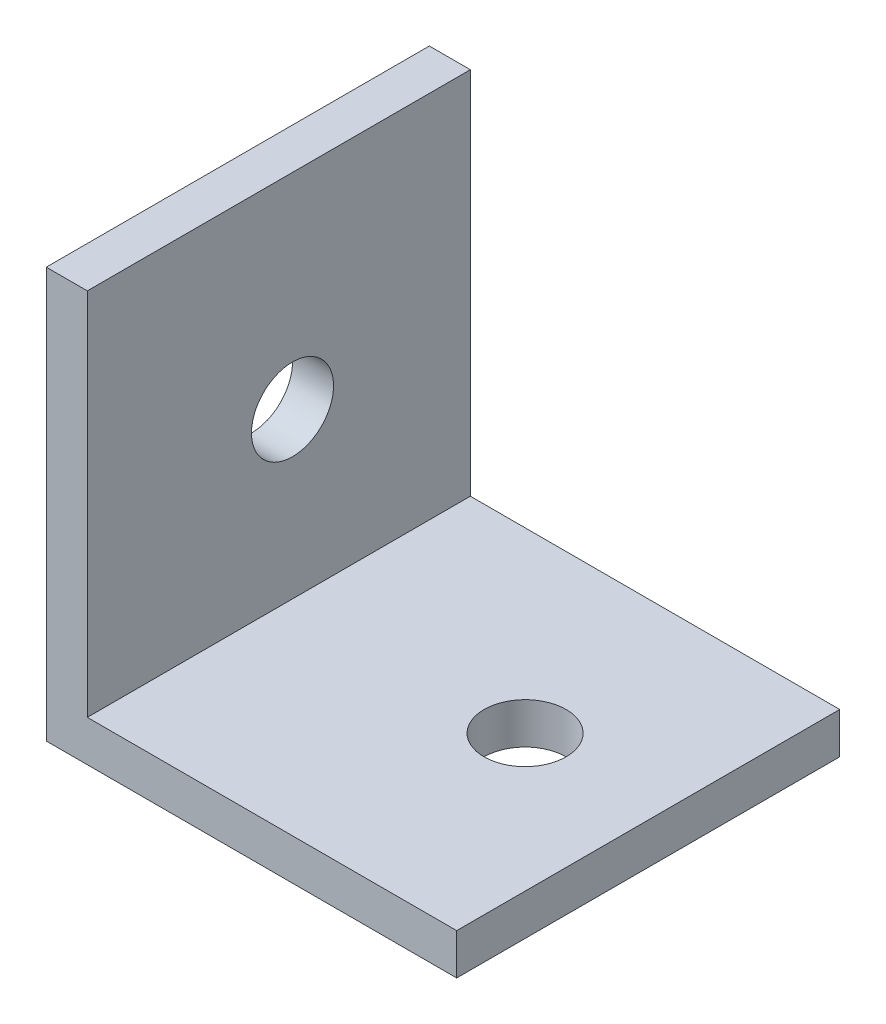
SolidWorks part; units mm, degrees
ref_plane "Plan de face" through (0, 0, 0) normal (0, 0, 1) x (1, 0, 0)
ref_plane "Plan de dessus" through (0, 0, 0) normal (0, 1, 0) x (1, 0, 0)
ref_plane "Plan de droite" through (0, 0, 0) normal (1, 0, 0) x (0, 0, -1)
sketch "Esquisse1" plane through (0, 0, 0) normal (0, 0, 1) x (1, 0, 0)
  line L0 (-18.0444, 3.8723) -> (-18.0444, -11.1277)
  line L1 (-18.0444, -11.1277) -> (-3.0444, -11.1277)
  line L2 (-3.0444, -11.1277) -> (-3.0444, -9.6277)
  line L3 (-3.0444, -9.6277) -> (-16.5444, -9.6277)
  line L4 (-16.5444, -9.6277) -> (-16.5444, 3.8723)
  line L5 (-16.5444, 3.8723) -> (-18.0444, 3.8723)
  dimension "D1" = 1.5
  dimension "D2" = 1.5
  dimension "D3" = 15
  dimension "D4" = 15
extrude "Extrusion1" add sketch "Esquisse1" along normal blind 14
sketch "Esquisse2" plane through (0, -9.6277, 0) normal (0, 1, 0) x (-1, 0, 0)
  line L0 (3.0444, 14) -> (3.0444, 0) construction
  line L1 (3.0444, 14) -> (16.5444, 14) construction
  circle A0 centre (8.0444, 6.5) radius 1.5
  point P2 (3.0444, 7)
  dimension "D1" = 5
  dimension "D2" = 7.5
extrude "Extrusion2" cut sketch "Esquisse2" against normal blind 14
sketch "Esquisse3" plane through (-18.0444, 0, 0) normal (-1, 0, 0) x (0, 0, 1)
  line L0 (14, 3.8723) -> (0, 3.8723) construction
  line L1 (14, 3.8723) -> (14, -11.1277) construction
  circle A0 centre (6.5, -3.6277) radius 1.5
  dimension "D1" = 7.5
  dimension "D2" = 7.5
extrude "Extrusion3" cut sketch "Esquisse3" against normal blind 14
